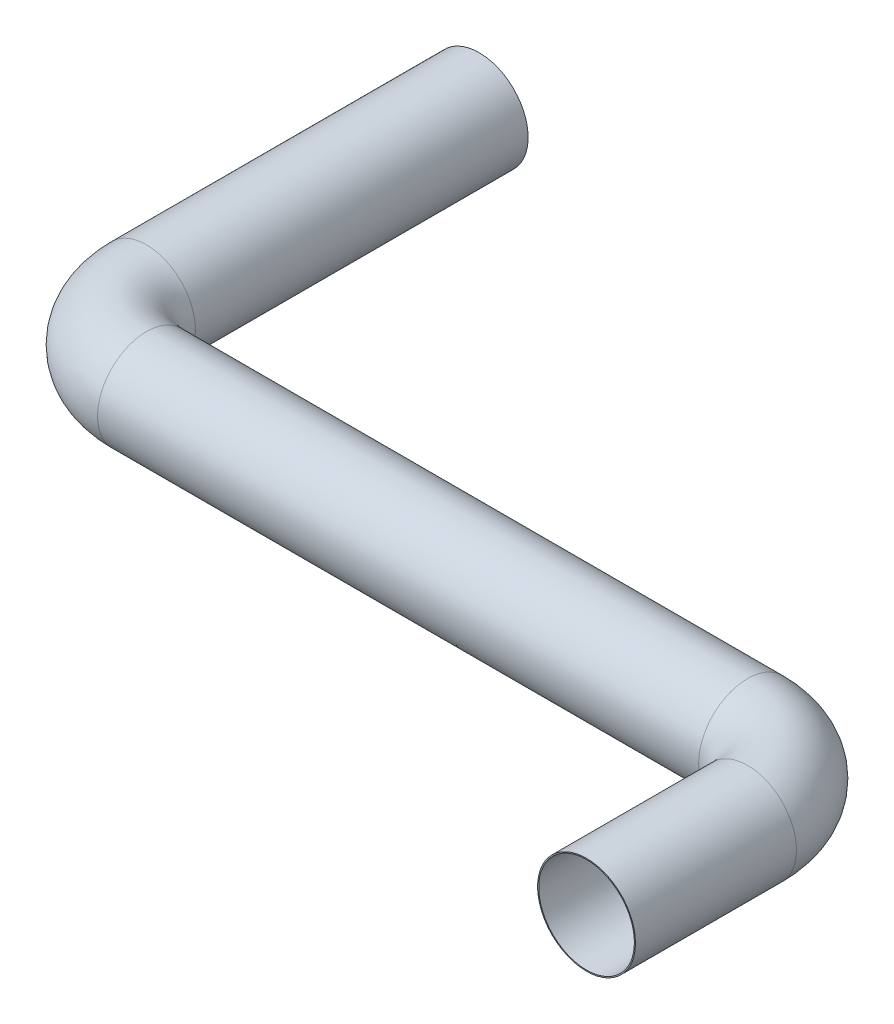
SolidWorks part; units mm, degrees
ref_plane "Front Plane" through (0, 0, 0) normal (0, 0, 1) x (1, 0, 0)
ref_plane "Top Plane" through (0, 0, 0) normal (0, 1, 0) x (1, 0, 0)
ref_plane "Right Plane" through (0, 0, 0) normal (1, 0, 0) x (0, 0, -1)
sketch "Sketch1" plane through (0, 0, 0) normal (0, 1, 0) x (1, 0, 0)
  line L0 (0, 0) -> (0, 150)
  line L1 (-70, 220) -> (-630, 220)
  line L2 (-700, 290) -> (-700, 470)
  arc A0 (-630, 220) -> (-700, 290) centre (-630, 290) cw
  arc A1 (0, 150) -> (-70, 220) centre (-70, 150) ccw
  point P7 (-700, 220)
  point P10 (0, 220)
  dimension "D4" = 70
  dimension "D5" = 70
  dimension "D1" = 700
  dimension "D2" = 220
  dimension "D3" = 250
sketch "Sketch2" plane through (0, 0, 0) normal (0, 0, 1) x (1, 0, 0)
  circle A0 centre (0, 0) radius 45.59
  circle A1 centre (0, 0) radius 44.59
  dimension "D1" = 89.18
  dimension "D2" = 91.18
sweep "Sweep1" add profiles "Sketch2" path "Sketch1"
sketch "Sketch3" plane through (0, 0, 0) normal (0, 0, 1) x (1, 0, 0)
  circle A0 centre (0, 0) radius 44.59
  circle A1 centre (0, 0) radius 45.59
sketch "Sketch4" plane through (0, 0, -470) normal (0, 0, -1) x (-1, 0, 0)
  circle A0 centre (700, 0) radius 44.59
  circle A1 centre (700, 0) radius 45.59
extrude "Boss-Extrude3" add sketch "Sketch4" along normal blind 130
